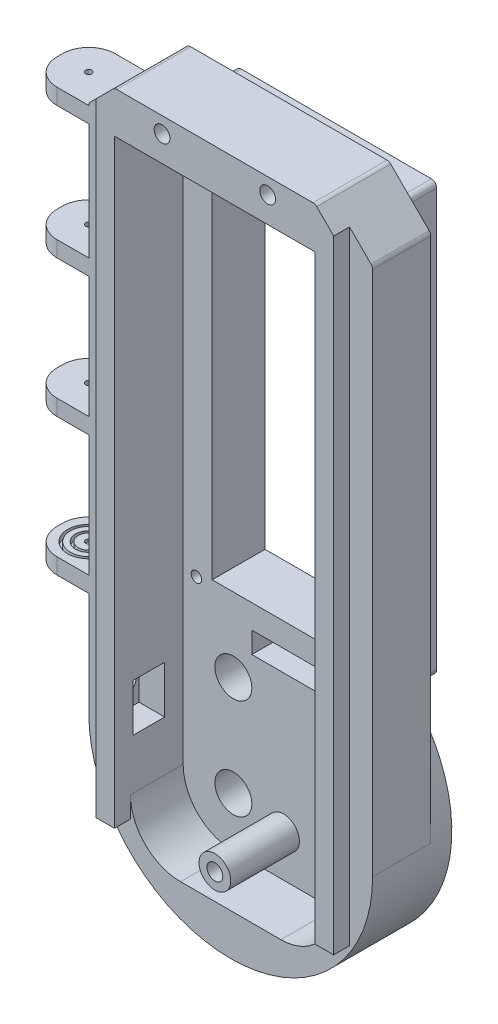
SolidWorks part; units mm, degrees
ref_plane "Alzado" through (0, 0, 0) normal (0, 0, 1) x (1, 0, 0)
ref_plane "Planta" through (0, 0, 0) normal (0, 1, 0) x (1, 0, 0)
ref_plane "Vista lateral" through (0, 0, 0) normal (1, 0, 0) x (0, 0, -1)
sketch "Croquis1" plane through (0, 0, 0) normal (0, 0, 1) x (1, 0, 0)
  line L1 (-19, -40.5) -> (19, -40.5)
  line L2 (-19, -40.5) -> (-19, 40.5)
  line L3 (-19, 40.5) -> (19, 40.5)
  line L4 (19, -40.5) -> (19, 40.5)
  line L5 (-19, -40.5) -> (19, 40.5) construction
  line L6 (-19, 40.5) -> (19, -40.5) construction
  line L7 (-19, -40.5) -> (19, -40.5)
  line L8 (-19, -40.5) -> (-19, -78.5)
  line L9 (-19, -78.5) -> (19, -78.5)
  line L10 (19, -40.5) -> (19, -78.5)
  line L13 (-13.5, 36) -> (13.5, 36)
  line L28 (13.5, 36) -> (13.5, -36)
  line L29 (-13.5, 36) -> (-13.5, -36)
  line L30 (-13.5, -36) -> (13.5, -36)
  circle A0 centre (-9.5, -50) radius 3.5
  circle A1 centre (9.5, -59.5) radius 3.5
  circle A2 centre (-9.5, -69) radius 3.5
  arc A3 (19, -40.5) -> (-19, -40.5) centre (0, -59.5) cw
  point P0 (0, 0)
  point P27 (9.5, -63)
  point P30 (9.5, -54.5)
  point P34 (-13.5, 0)
extrude "Saliente-Extruir1" add sketch "Croquis1" along normal blind 5 contours L1 L4 L3 L2 L30 L29 L13 L28 | L10 L1 L8 L9 A2 A1 A0 | A3 L10 | A3 L9 | A3 L8
sketch "Croquis2" plane through (0, 0, 0) normal (0, 0, -1) x (-1, 0, 0)
  line L0 (-19, 40.5) -> (19, 40.5)
  line L1 (19, -40.5) -> (-19, -40.5)
  line L2 (-19, -40.5) -> (-19, 40.5)
  line L4 (19, -40.5) -> (19, 40.5)
  line L5 (-13.5, 36) -> (-13.5, -36)
  line L7 (-13.5, -36) -> (13.5, -36)
  line L8 (13.5, -36) -> (13.5, 36)
  line L9 (13.5, 36) -> (-13.5, 36)
extrude "Saliente-Extruir2" add sketch "Croquis2" along normal blind 5
sketch "Croquis3" plane through (0, 0, 5) normal (0, 0, 1) x (1, 0, 0)
  line L0 (26.8701, -59.5) -> (26.8701, 40.5)
  line L1 (19, -59.5) -> (19, 40.5)
  line L2 (19, 40.5) -> (-19, 40.5)
  line L3 (-19, 40.5) -> (-19, -59.5)
  line L4 (26.8701, 40.5) -> (19, 48.3701)
  line L5 (19, 48.3701) -> (-19, 48.3701)
  line L6 (-19, 48.3701) -> (-26.8701, 40.5)
  line L7 (-26.8701, 40.5) -> (-26.8701, -59.5)
  arc A2 (-19, -59.5) -> (19, -59.5) centre (0, -59.5) ccw
  arc A3 (-26.8701, -59.5) -> (26.8701, -59.5) centre (0, -59.5) ccw
extrude "Saliente-Extruir9" add sketch "Croquis3" against normal blind 1
sketch "Croquis4" plane through (0, 0, 4) normal (0, 0, -1) x (-1, 0, 0)
  line L0 (-19, 40.5) -> (-19, -40.5)
  line L1 (-19, 40.5) -> (19, 40.5)
  line L2 (19, 40.5) -> (19, -40.5)
  line L3 (14, -77) -> (-14, -77)
  line L4 (-19, -72) -> (-19, -41.338)
  line L5 (19, -72) -> (19, -40.5)
  line L6 (-26.8701, 40.5) -> (-19, 48.3701)
  line L7 (-19, 48.3701) -> (19, 48.3701)
  line L8 (19, 48.3701) -> (26.8701, 40.5)
  line L9 (26.8701, 40.5) -> (26.8701, -59.5)
  line L10 (-26.8701, 40.5) -> (-26.8701, -59.5)
  arc A0 (-19, -40.5) -> (-26.8701, -59.5) centre (0, -59.5) ccw construction
  arc A1 (-14, -77) -> (-19, -72) centre (-14, -72) cw
  arc A2 (14, -77) -> (19, -72) centre (14, -72) ccw
  arc A3 (-19, -40.5) -> (19, -40.5) centre (0, -59.5) ccw construction
  arc A4 (-26.8701, -59.5) -> (26.8701, -59.5) centre (0, -59.5) ccw
  arc M1 (19, -40.5) -> (26.8701, -59.5) centre (0, -59.5) cw
  line M2 (26.8701, -59.5) -> (26.8701, 40.5)
  line M3 (26.8701, 40.5) -> (19, 48.3701)
  line M4 (19, 48.3701) -> (-19, 48.3701)
  line M5 (-19, 48.3701) -> (-26.8701, 40.5)
  line M6 (-26.8701, 40.5) -> (-26.8701, -59.5)
  arc M7 (-26.8701, -59.5) -> (-19, -40.5) centre (0, -59.5) cw
  line M8 (-19, -40.5) -> (-19, 40.5)
  line M9 (-19, 40.5) -> (19, 40.5)
  line M10 (19, 40.5) -> (19, -40.5)
  dimension "D1" = 5
extrude "Saliente-Extruir10" add sketch "Croquis4" against normal blind 11 contours M10 M1 M2 M3 M4 M5 M6 M7 M8 M9
sketch "Croquis5" plane through (0, 0, 5) normal (0, 0, 1) x (1, 0, 0)
  line L0 (-19, -59.5) -> (-19, -69)
  line L1 (19, -69) -> (19, -59.5)
  line L2 (9.5, -78.5) -> (-9.5, -78.5)
  line L3 (19, -59.5) -> (19, -40.5)
  line L4 (-19, -59.5) -> (-19, -40.5)
  arc A0 (-19, -40.5) -> (19, -40.5) centre (0, -59.5) ccw
  arc A1 (-9.5, -78.5) -> (-19, -69) centre (-9.5, -69) cw
  arc A2 (9.5, -78.5) -> (19, -69) centre (9.5, -69) ccw
extrude "Saliente-Extruir11" add sketch "Croquis5" along normal blind 10
fillet "Redondeo1" radius 1 4 edges at (-19, -40.5, -2.5) (-19, 40.5, -0.5) (19, 40.5, -0.5) (19, -40.5, -2.5)
fillet "Redondeo2" radius 1 5 edges at (-18.7071, 40.2071, 4) (18.7071, 40.2071, 4) (-19, -0.5, 4) (0, 40.5, 4) (19, -0.5, 4)
fillet "Redondeo3" radius 1 4 edges at (-26.8701, 40.5, 9.5) (-19, 48.3701, 9.5) (26.8701, 40.5, 9.5) (19, 48.3701, 9.5)
sketch "Croquis6" plane through (-26.8701, 0, 0) normal (-1, 0, 0) x (0, 0, 1)
  line L2 (8.5, -50.5) -> (14.5, -50.5)
  line L3 (14.5, -50.5) -> (14.5, -59.5)
  line L4 (14.5, -59.5) -> (8.5, -59.5)
  line L5 (8.5, -50.5) -> (8.5, -59.5)
extrude "Cortar-Extruir1" cut sketch "Croquis6" against normal blind 8
sketch "Croquis7" plane through (-26.8701, 0, 0) normal (-1, 0, 0) x (0, 0, 1)
  line L0 (8.5, -50.5) -> (14.5, -50.5)
  line L1 (14.5, -50.5) -> (14.5, -59.5)
  line L2 (14.5, -59.5) -> (8.5, -59.5)
  line L3 (8.5, -59.5) -> (8.5, -50.5)
  circle A0 centre (11.5, -55) radius 2.5
extrude "Saliente-Extruir12" add sketch "Croquis7" against normal blind 3
sketch "Croquis8" plane through (-26.8701, 0, 0) normal (-1, 0, 0) x (0, 0, 1)
  line L0 (4, 40.0858) -> (4, 37.0858)
  line L1 (4, 39.5) -> (4, -41.5556) construction
  line L2 (4, 37.0858) -> (15, 37.0858)
  line L3 (15, -59.5) -> (15, 40.0858) construction
  line L4 (15, 37.0858) -> (15, 40.0858)
  line L5 (15, 40.0858) -> (4, 40.0858)
  line L6 (9.5, 37.0858) -> (9.5, 15.0858)
  line L7 (9.5, 15.0858) -> (15, 15.0858)
  line L8 (9.5, 15.0858) -> (4, 15.0858)
  line L9 (4, 15.0858) -> (4, 12.0858)
  line L10 (4, 40.0858) -> (4, -59.5) construction
  line L11 (4, 12.0858) -> (15, 12.0858)
  line L12 (15, 12.0858) -> (15, 15.0858)
  line L13 (9.5, 12.0858) -> (9.5, -10.9142)
  line L14 (9.5, -10.9142) -> (15, -10.9142)
  line L15 (15, -10.9142) -> (15, -13.9142)
  line L16 (15, -13.9142) -> (4, -13.9142)
  line L17 (4, -13.9142) -> (4, -10.9142)
  line L18 (4, -10.9142) -> (9.5, -10.9142)
  line L19 (9.5, -13.9142) -> (9.5, -36.9142)
  line L20 (9.5, -36.9142) -> (15, -36.9142)
  line L21 (15, -36.9142) -> (15, -39.9142)
  line L22 (15, -39.9142) -> (4, -39.9142)
  line L23 (4, -39.9142) -> (4, -36.9142)
  line L24 (4, -36.9142) -> (9.5, -36.9142)
  line M2 (15, -59.5) -> (15, 40.0858)
  line M3 (15, 40.0858) -> (4, 40.0858)
  line M4 (4, 40.0858) -> (4, -59.5)
extrude "Saliente-Extruir13" add sketch "Croquis8" along normal blind 11 contours L2 M4 M2 M3 | L11 L7 L8 M4 M2 | L18 L16 L14 M4 M2 | L24 L22 L20 M4 M2
fillet "Redondeo4" radius 5 8 edges at (-37.8701, 38.5858, 4) (-37.8701, 38.5858, 15) (-37.8701, 13.5858, 4) (-37.8701, 13.5858, 15) (-37.8701, -12.4142, 4) (-37.8701, -12.4142, 15) (-37.8701, -38.4142, 4) (-37.8701, -38.4142, 15)
sketch "Croquis9" plane through (0, 40.0858, 0) normal (0, 1, 0) x (1, 0, 0)
  circle A0 centre (-32.3701, -9.5) radius 0.6
extrude "Cortar-Extruir2" cut sketch "Croquis9" against normal blind 80
sketch "Croquis10" plane through (0, -39.9142, 0) normal (0, -1, 0) x (1, 0, 0)
  circle A0 centre (-32.3701, 9.5) radius 0.6
extrude "Saliente-Extruir14" add sketch "Croquis10" against normal blind 2.5
sketch "Croquis11" plane through (0, -36.9142, 0) normal (0, 1, 0) x (1, 0, 0)
  circle A0 centre (-32.3701, -9.5) radius 2
  circle A1 centre (-32.3701, -9.5) radius 2.5
  circle A2 centre (-32.3701, -9.5) radius 3.5
  circle A3 centre (-32.3701, -9.5) radius 4
extrude "Cortar-Extruir3" cut sketch "Croquis11" against normal blind 1 contours A3 A2 | A1 A0
sketch "Croquis13" plane through (0, 0, 15) normal (0, 0, 1) x (1, 0, 0)
  line L0 (19, 40.5) -> (22.5, 40.5)
  line L1 (19, -69) -> (22.5, -69)
  line L2 (22.5, -69) -> (22.5, 40.5)
  line L3 (19, -69) -> (19, 40.5)
  line L5 (22.5, 40.5) -> (22.5, 44.8701)
  line L6 (-19, -69) -> (-19, 40.5)
  line L7 (-22.5, -69) -> (-22.5, 40.5)
  line L8 (-19, -69) -> (-22.5, -69)
  line L9 (-19, 40.5) -> (-22.5, 40.5)
  line L10 (-19, -69) -> (-19, -65.5)
  line L12 (19, -65.5) -> (19, -69)
  line L13 (-22.5, 40.5) -> (-22.5, 44.8701)
  line L14 (-26.5772, 40.7929) -> (-19.2929, 48.0772) construction
  line L15 (-22.5, 44.8701) -> (-19.2929, 48.0772)
  line L16 (-18.5858, 48.3701) -> (18.5858, 48.3701)
  line L19 (22.5, 44.8701) -> (19.2929, 48.0772)
  arc A0 (-19.2929, 48.0772) -> (-18.5858, 48.3701) centre (-18.5858, 47.3701) cw
  arc A1 (19.2929, 48.0772) -> (18.5858, 48.3701) centre (18.5858, 47.3701) ccw
  line M1 (19, 40.5) -> (19, -69)
  line M5 (-19, -69) -> (-19, 40.5)
  line M6 (-19, 40.5) -> (19, 40.5)
  line M14 (26.5772, 40.7929) -> (19.2929, 48.0772)
  arc M15 (19.2929, 48.0772) -> (18.5858, 48.3701) centre (18.5858, 47.3701) ccw
  line M16 (18.5858, 48.3701) -> (-18.5858, 48.3701)
  arc M17 (-18.5858, 48.3701) -> (-19.2929, 48.0772) centre (-18.5858, 47.3701) ccw
  line M18 (-19.2929, 48.0772) -> (-26.5772, 40.7929)
extrude "Saliente-Extruir15" add sketch "Croquis13" along normal blind 3 contours L6 L9 L7 L8 M5 | L1 L2 L0 L3 M1 | L13 L9 L0 L5 M6 M14 M15 M16 M17 M18
sketch "Croquis14" plane through (0, 0, 4) normal (0, 0, -1) x (-1, 0, 0)
  circle A0 centre (10, 45.3701) radius 1.5
  circle A1 centre (-10, 45.3701) radius 1.5
extrude "Cortar-Extruir4" cut sketch "Croquis14" against normal blind 14
sketch "Croquis16" plane through (0, -69, 0) normal (0, -1, 0) x (-1, 0, 0)
  line L1 (22.5, -15) -> (19, -15)
  line L2 (22.5, -15) -> (22.5, -18)
  line L3 (22.5, -18) -> (19, -18)
  line L4 (-19, -15) -> (-22.5, -15)
  line L5 (-19, -15) -> (-19, -18)
  line L6 (-19, -18) -> (-22.5, -18)
  line L7 (-22.5, -15) -> (-22.5, -18)
  line L8 (19, -15) -> (19, -18)
extrude "Saliente-Extruir16" add sketch "Croquis16" along normal blind 4
sketch "Croquis25" plane through (0, 0, 18) normal (0, 0, 1) x (1, 0, 0)
  line L0 (-10, 45.3701) -> (10, 45.3701)
  line L1 (0, 45.3701) -> (0, -70.6299)
  circle A0 centre (0, -70.6299) radius 3
  circle A1 centre (0, -70.6299) radius 1.5
extrude "Saliente-Extruir21" add sketch "Croquis25" against normal blind 18
sketch "Croquis26" plane through (0, 0, 18) normal (0, 0, 1) x (1, 0, 0)
  circle A0 centre (0, -70.6299) radius 1.5
extrude "Cortar-Extruir7" cut sketch "Croquis26" against normal blind 18
sketch "Croquis28" plane through (0, 0, 5) normal (0, 0, 1) x (1, 0, 0)
  circle A0 centre (-16.5, 38) radius 1
  circle A1 centre (14.5, 38) radius 1
  circle A2 centre (14.5, -37) radius 1
  circle A3 centre (-16.5, -37) radius 1
extrude "Cortar-Extruir8" cut sketch "Croquis28" against normal blind 4
sketch "Croquis29" plane through (0, 0, 5) normal (0, 0, 1) x (1, 0, 0)
  line L2 (-6, -40.5) -> (10, -40.5)
  line L3 (10, -40.5) -> (10, -44.5)
  line L4 (10, -44.5) -> (-6, -44.5)
  line L6 (-6, -40.5) -> (-6, -44.5)
extrude "Cortar-Extruir9" cut sketch "Croquis29" against normal up to surface (5 mm away) up to face at (1.5, -70.6299, 0)
